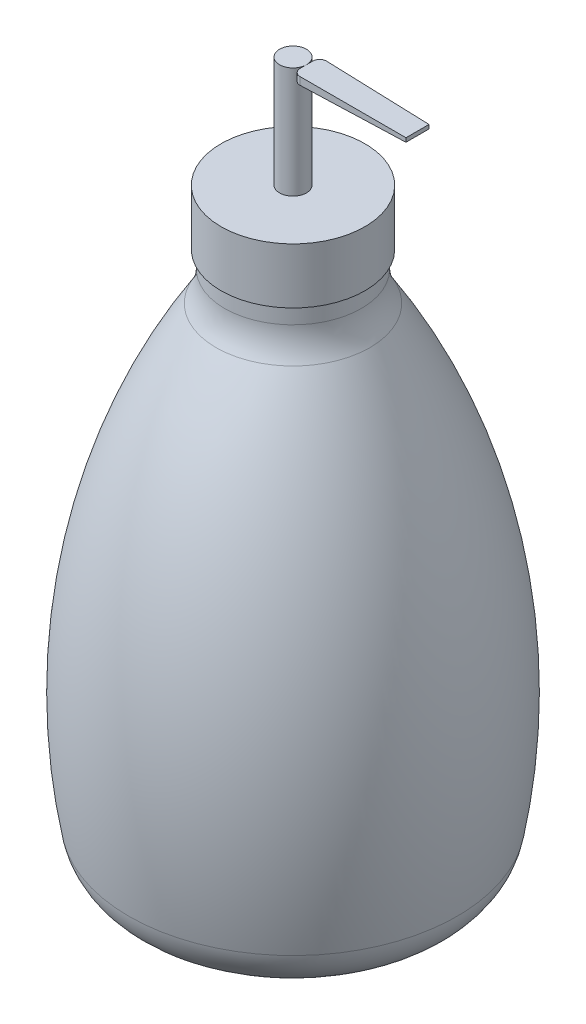
SolidWorks part; units mm, degrees
ref_plane "Front Plane" through (0, 0, 0) normal (0, 0, 1) x (1, 0, 0)
ref_plane "Top Plane" through (0, 0, 0) normal (0, 1, 0) x (1, 0, 0)
ref_plane "Right Plane" through (0, 0, 0) normal (1, 0, 0) x (0, 0, -1)
sketch "Sketch1" plane through (0, 0, 0) normal (0, 0, 1) x (1, 0, 0)
  line L0 (0, 58.1406) -> (0, -43.4594) construction
  line L1 (0, -43.4594) -> (-28.1944, -43.4594)
  line L2 (0, 58.1406) -> (-12.5123, 58.1406)
  line L3 (-12.5123, 58.1406) -> (-12.5123, 49.4654)
  line L4 (0, 58.1406) -> (0, -43.4594)
  arc A0 (-12.5123, 49.4654) -> (-28.1944, -43.4594) centre (83.5167, -14.5263) ccw
  dimension "D1" = 101.6
revolve "Revolve1" add sketch "Sketch1" angle 360 about L0
fillet "Fillet1" radius 10.16 2 edges at (0, 49.4654, 12.5123) (0, -43.4594, 28.1944)
sketch "Sketch2" plane through (0, 58.1406, 0) normal (0, 1, 0) x (1, 0, 0)
  circle A0 centre (0, 0) radius 13.1649
extrude "Boss-Extrude1" add sketch "Sketch2" along normal blind 7.62 and the other way blind 2.54 separate body
sketch "Sketch3" plane through (0, 65.7606, 0) normal (0, 1, 0) x (1, 0, 0)
  circle A0 centre (0, 0) radius 2.4608
extrude "Boss-Extrude2" add sketch "Sketch3" along normal blind 20.32
ref_plane "Plane1" through (2.4608, 0, 0) normal (1, 0, 0) x (0, 0, -1)
sketch "Sketch4" plane through (2.4608, 0, 0) normal (1, 0, 0) x (0, 0, -1)
  line L0 (2.4608, 65.7606) -> (2.4608, 86.0806) construction
  line L1 (-2.4608, 86.0806) -> (2.4608, 86.0806)
  line L2 (-2.4608, 86.0806) -> (-2.4608, 84.6471)
  line L3 (-2.4608, 84.6471) -> (2.4608, 84.6471)
  line L4 (2.4608, 86.0806) -> (2.4608, 84.6471)
extrude "Boss-Extrude3" add sketch "Sketch4" along normal blind 20.32 draft 1 separate body
fillet "Fillet2" radius 1.27 2 edges at (2.4608, 85.3638, -2.4608) (2.4608, 85.3638, 2.4608)
